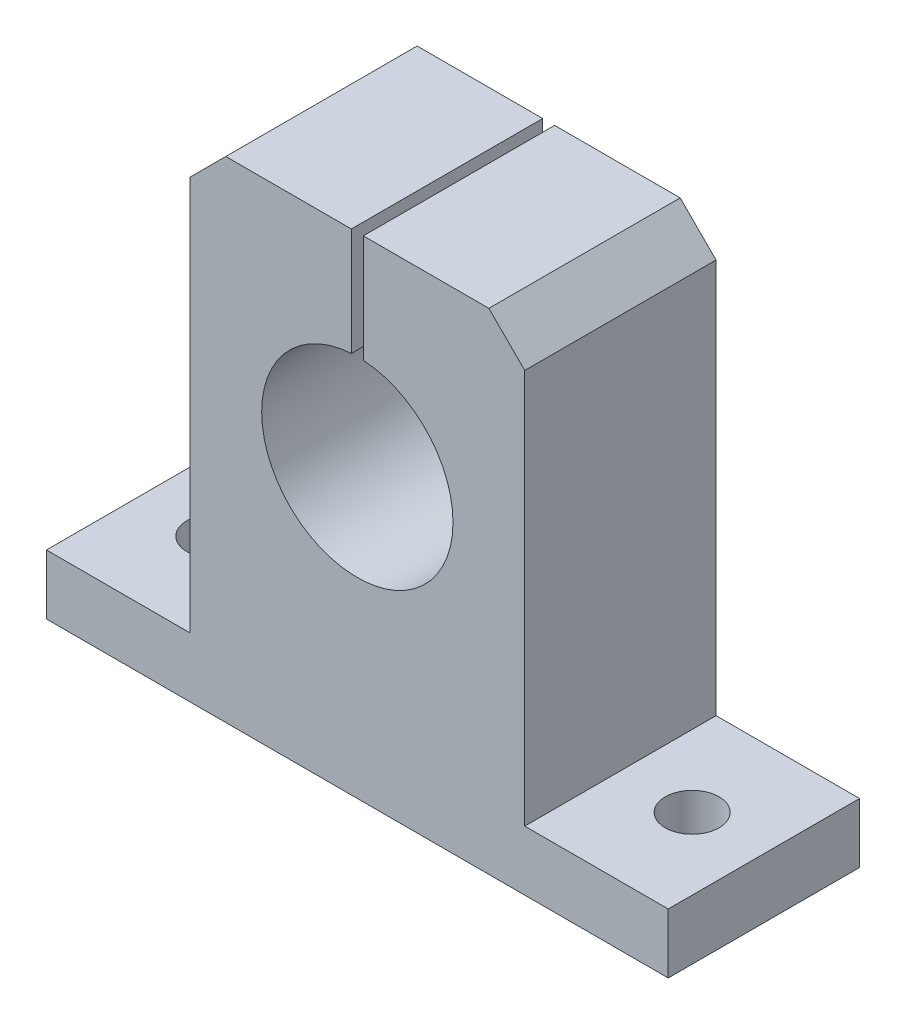
SolidWorks part; units mm, degrees
ref_plane "Front" through (0, 0, 0) normal (0, 0, 1) x (1, 0, 0)
ref_plane "Top" through (0, 0, 0) normal (0, 1, 0) x (1, 0, 0)
ref_plane "Right" through (0, 0, 0) normal (1, 0, 0) x (0, 0, -1)
sketch "Sketch1" plane through (0, 0, 0) normal (0, 0, 1) x (1, 0, 0)
  line L0 (22.225, 26.9875) -> (0.7938, 26.9875)
  line L1 (0.7938, 26.9875) -> (0.7938, 12.6752)
  line L2 (22.225, 26.9875) -> (22.225, -30.1625)
  line L3 (22.225, -30.1625) -> (41.275, -30.1625)
  line L4 (41.275, -30.1625) -> (41.275, -38.1)
  line L5 (41.275, -38.1) -> (-41.275, -38.1)
  line L6 (-41.275, -38.1) -> (-41.275, -30.1625)
  line L7 (-41.275, -30.1625) -> (-22.225, -30.1625)
  line L8 (-22.225, -30.1625) -> (-22.225, 26.9875)
  line L9 (-22.225, 26.9875) -> (-0.7937, 26.9875)
  line L10 (-0.7937, 26.9875) -> (-0.7937, 12.6752)
  arc A0 (-0.7937, 12.6752) -> (0.7938, 12.6752) centre (0, 0) ccw
  dimension "D2" = 12.7
  dimension "D4" = 38.1
  dimension "D1" = 82.55
  dimension "D3" = 65.0875
  dimension "D5" = 7.9375
  dimension "D6" = 44.45
  dimension "D7" = 1.5875
extrude "Extrude1" add sketch "Sketch1" along normal mid plane 25.4
hole_wizard "1/4 Clearance Hole1" positions "Sketch3" profile "Sketch2" hole size "1/4" standard "Ansi Inch" end condition up to next
sketch "Sketch3" plane through (0, -38.1, 0) normal (0, -1, 0) x (1, 0, 0)
  point P0 (-31.75, 0)
  point P1 (31.75, 0)
  dimension "D1" = 63.5
  dimension "D2" = 31.75
sketch "Sketch2" plane through (-31.75, -38.1, 0) normal (1, 0, 0) x (0, 0, -1)
  line L0 (0, 0) -> (0, 7.9375)
  line L1 (0, 7.9375) -> (3.5712, 7.9375)
  line L2 (3.5712, 7.9375) -> (3.5712, 0)
  line L5 (3.5712, 0) -> (0, 0)
  line L11 (0, -6.35) -> (0, 107.95) construction
  dimension "Thru Hole Dia." = 7.1425
  dimension "Thru Hole Depth" = 7.9375
chamfer "Chamfer1" distance 4.7625 angle 45 2 edges at (-22.225, 26.9875, 0) (22.225, 26.9875, 0)
